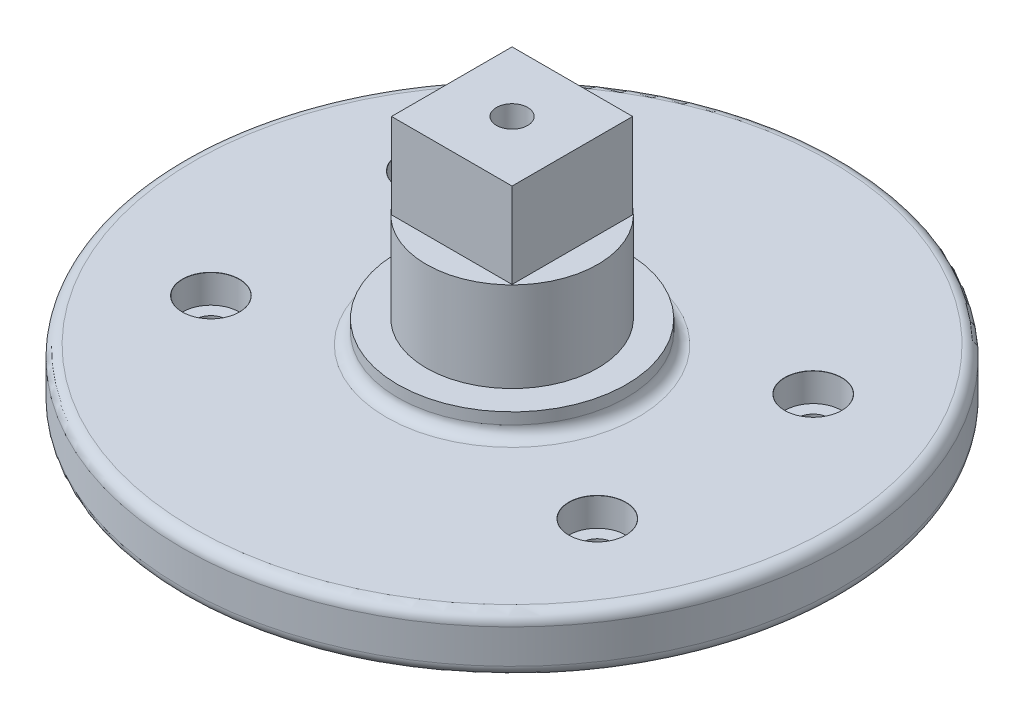
SolidWorks part; units mm, degrees
ref_plane "Front Plane" through (0, 0, 0) normal (0, 0, 1) x (1, 0, 0)
ref_plane "Top Plane" through (0, 0, 0) normal (0, 1, 0) x (1, 0, 0)
ref_plane "Right Plane" through (0, 0, 0) normal (1, 0, 0) x (0, 0, -1)
sketch "Sketch1" plane through (0, 0, 0) normal (0, 1, 0) x (1, 0, 0)
  circle A0 centre (0, 0) radius 58
  dimension "D1" = 116
extrude "Boss-Extrude1" add sketch "Sketch1" along normal blind 10
hole_wizard "CBORE for M5 SHCS3" positions "Sketch2" profile "Sketch3" counterbore size "M5" standard "ANSI Metric" end condition through all
sketch "Sketch2" plane through (0, 10, 0) normal (0, 1, 0) x (1, 0, 0)
  line L0 (-34, 19) -> (34, 19) construction
  line L1 (34, 19) -> (34, -19) construction
  line L2 (34, -19) -> (-34, -19) construction
  line L3 (-34, -19) -> (-34, 19) construction
  point P0 (-34, 19)
  point P2 (34, 19)
  point P4 (-34, -19)
  point P6 (34, -19)
  point P16 (0, -19)
  point P18 (-34, 0)
  dimension "D1" = 38
  dimension "D2" = 68
sketch "Sketch3" plane through (-34, 10, -19) normal (1, 0, 0) x (0, 0, 1)
  line L0 (0, 0) -> (0, 10)
  line L1 (0, 10) -> (2.75, 10)
  line L3 (2.75, 10) -> (2.75, 5)
  line L4 (5, 5) -> (2.75, 5)
  line L5 (5, 5) -> (5, 0.025)
  line L6 (5, 0.025) -> (5.025, 0)
  line L7 (5.025, 0) -> (0, 0)
  line L8 (-5, 0.025) -> (-5.025, 0) construction
  line L11 (0, -6.35) -> (0, 107.95) construction
  dimension "Thru Hole Dia." = 5.5
  dimension "Thru Hole Depth" = 10
  dimension "C'Bore Dia." = 10
  dimension "C'Bore Depth" = 5
  dimension "Near C'Sink Dia." = 10.05
  dimension "Near C'Sink Angle" = 90
sketch "Sketch5" plane through (0, 10, 0) normal (0, 1, 0) x (1, 0, 0)
  circle A0 centre (0, 0) radius 20.125
  dimension "D1" = 40.25
extrude "Boss-Extrude3" add sketch "Sketch5" along normal blind 4
sketch "Sketch4" plane through (0, 14, 0) normal (0, 1, 0) x (1, 0, 0)
  circle A0 centre (0, 0) radius 15.1
  dimension "D1" = 30.2
extrude "Boss-Extrude2" add sketch "Sketch4" along normal blind 15.8
fillet "Fillet1" radius 2 2 edges at (0, 0, 58) (0, 10, 58)
fillet "Fillet2" radius 2 1 edges at (0, 10, 20.125)
sketch "Sketch7" plane through (0, 29.8, 0) normal (0, 1, 0) x (1, 0, 0)
  line L1 (-10.6066, -10.6066) -> (10.6066, -10.6066)
  line L2 (-10.6066, -10.6066) -> (-10.6066, 10.6066)
  line L3 (-10.6066, 10.6066) -> (10.6066, 10.6066)
  line L4 (10.6066, -10.6066) -> (10.6066, 10.6066)
  line L5 (-10.6066, -10.6066) -> (10.6066, 10.6066) construction
  line L6 (-10.6066, 10.6066) -> (10.6066, -10.6066) construction
  circle A0 centre (0, 0) radius 15 construction
  point P7 (-10.6066, 10.6066)
  dimension "D1" = 30
extrude "Boss-Extrude4" add sketch "Sketch7" along normal blind 15
hole_wizard "M5 Clearance Hole1" positions "Sketch8" profile "Sketch9" hole size "M5" standard "ANSI Metric" end condition up to next
sketch "Sketch8" plane through (0, 0, 0) normal (0, -1, 0) x (-1, 0, 0)
  point P0 (0, 0)
sketch "Sketch9" plane through (0, 0, 0) normal (1, 0, 0) x (0, 0, -1)
  line L0 (0, 0) -> (0, 44.8)
  line L1 (0, 44.8) -> (2.75, 44.8)
  line L2 (2.75, 44.8) -> (2.75, 0.025)
  line L3 (2.75, 0.025) -> (2.775, 0)
  line L5 (2.775, 0) -> (0, 0)
  line L6 (-2.75, 0.025) -> (-2.775, 0) construction
  line L11 (0, -6.35) -> (0, 107.95) construction
  dimension "Thru Hole Dia." = 5.5
  dimension "Thru Hole Depth" = 44.8
  dimension "Near C'Sink Dia." = 5.55
  dimension "Near C'Sink Angle" = 90
sketch "Sketch10" plane through (0, 0, 0) normal (0, -1, 0) x (1, 0, 0)
  line L1 (2.3671, 4.1) -> (-2.3671, 4.1)
  line L2 (-2.3671, 4.1) -> (-4.7343, 0)
  line L3 (-4.7343, 0) -> (-2.3671, -4.1)
  line L4 (-2.3671, -4.1) -> (2.3671, -4.1)
  line L5 (2.3671, -4.1) -> (4.7343, 0)
  line L6 (4.7343, 0) -> (2.3671, 4.1)
  circle A1 centre (0, 0) radius 4.1 construction
  point P1 (0, 4.1)
  dimension "D1" = 8.2
extrude "Cut-Extrude1" cut sketch "Sketch10" against normal blind 3.8
